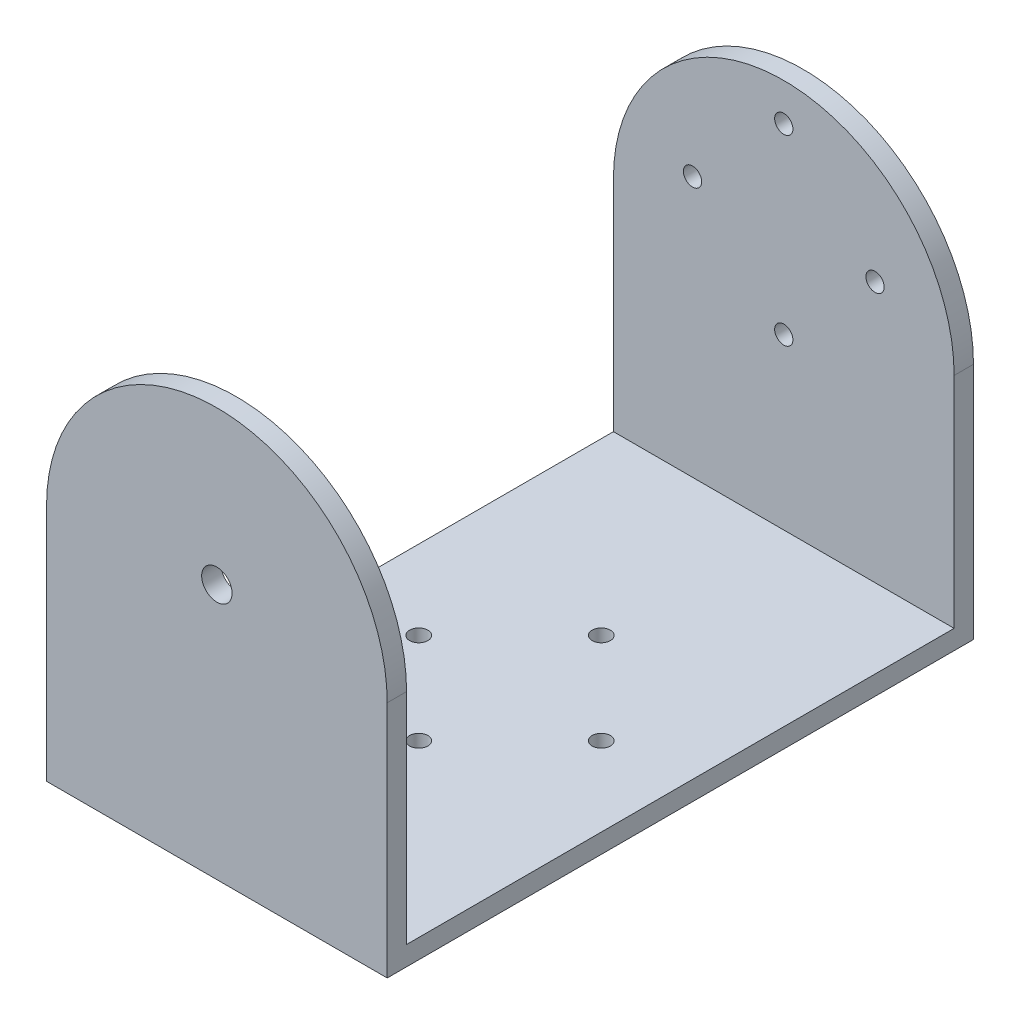
SolidWorks part; units mm, degrees
material "6061 Alloy"
ref_plane "Front Plane" through (0, 0, 0) normal (0, 0, 1) x (1, 0, 0)
ref_plane "Top Plane" through (0, 0, 0) normal (0, 1, 0) x (1, 0, 0)
ref_plane "Right Plane" through (0, 0, 0) normal (1, 0, 0) x (0, 0, -1)
sketch "Sketch1" plane through (0, 0, 0) normal (0, 1, 0) x (1, 0, 0)
  line L0 (-10.3213, 0) -> (10.2545, 0) construction
  line L1 (-14, 24.09) -> (14, 24.09)
  line L2 (-14, 24.09) -> (-14, -24.09)
  line L3 (-14, -24.09) -> (14, -24.09)
  line L4 (14, 24.09) -> (14, -24.09)
  line L5 (-14, 24.09) -> (14, -24.09) construction
  line L6 (-14, -24.09) -> (14, 24.09) construction
  line L7 (0, 8.8203) -> (0, -9.4436) construction
  circle A0 centre (0, 0) radius 12 construction
  circle A1 centre (0, 7.5) radius 0.75
  circle A2 centre (0, -7.5) radius 0.75
  circle A3 centre (7.5, 0) radius 0.75
  circle A4 centre (-7.5, 0) radius 0.75
  point P0 (0, 0)
  dimension "D1" = 24
  dimension "D6" = 1.5
  dimension "D2" = 7.5
  dimension "D3" = 15
  dimension "D4" = 7.5
  dimension "D5" = 15
  dimension "D7" = 48.18
  dimension "D8" = 28
extrude "Boss-Extrude1" add sketch "Sketch1" along normal blind 1.59
sketch "Sketch2" plane through (0, 1.59, 0) normal (0, 1, 0) x (1, 0, 0)
  line L0 (14, -24.09) -> (14, 24.09) construction
  line L1 (-14, 24.09) -> (14, 24.09)
  line L2 (-14, 24.09) -> (-14, 22.5)
  line L3 (-14, 22.5) -> (14, 22.5)
  line L4 (14, 24.09) -> (14, 22.5)
  line L6 (-14, -24.09) -> (14, -24.09)
  line L7 (-14, -24.09) -> (-14, -22.5)
  line L8 (-14, -22.5) -> (14, -22.5)
  line L9 (14, -24.09) -> (14, -22.5)
  dimension "D1" = 1.59
  dimension "D2" = 1.59
extrude "Boss-Extrude2" add sketch "Sketch2" along normal blind 18
sketch "Sketch3" plane through (0, 0, 24.09) normal (0, 0, 1) x (1, 0, 0)
  line L0 (-14, 19.59) -> (14, 19.59) construction
  line L1 (-14, 19.59) -> (-14, 0) construction
  line L2 (-14, 19.59) -> (14, 19.59)
  arc A0 (14, 19.59) -> (-14, 19.59) centre (0, 19.59) ccw
extrude "Boss-Extrude3" add sketch "Sketch3" against normal up to surface (1.59 mm away) up to face at (0, 10.59, 22.5)
sketch "Sketch4" plane through (0, 0, -24.09) normal (0, 0, -1) x (-1, 0, 0)
  line L0 (-14, 19.59) -> (14, 19.59) construction
  line L1 (-14, 19.59) -> (-14, 0) construction
  line L2 (-14, 19.59) -> (14, 19.59)
  arc A0 (14, 19.59) -> (-14, 19.59) centre (0, 19.59) ccw
extrude "Boss-Extrude4" add sketch "Sketch4" against normal up to surface (1.59 mm away) up to face at (0, 10.59, -22.5)
sketch "Sketch5" plane through (0, 0, 24.09) normal (0, 0, 1) x (1, 0, 0)
  circle A0 centre (0, 21) radius 1.25
  dimension "D2" = 2.5
  dimension "D1" = 21
extrude "Cut-Extrude1" cut sketch "Sketch5" against normal blind 6
sketch "Sketch6" plane through (0, 0, -24.09) normal (0, 0, -1) x (-1, 0, 0)
  circle A0 centre (0, 23) radius 7.5 construction
  circle A1 centre (0, 30.5) radius 0.75
  circle A2 centre (0, 15.5) radius 0.75
  circle A3 centre (7.5, 23) radius 0.75
  circle A4 centre (-7.5, 23) radius 0.75
  dimension "D2" = 15
  dimension "D3" = 1.5
  dimension "D1" = 23
extrude "Cut-Extrude2" cut sketch "Sketch6" against normal blind 6
sketch "Sketch7" plane through (0, 1.59, 0) normal (0, 1, 0) x (1, 0, 0)
  point P0 (0, 0)
